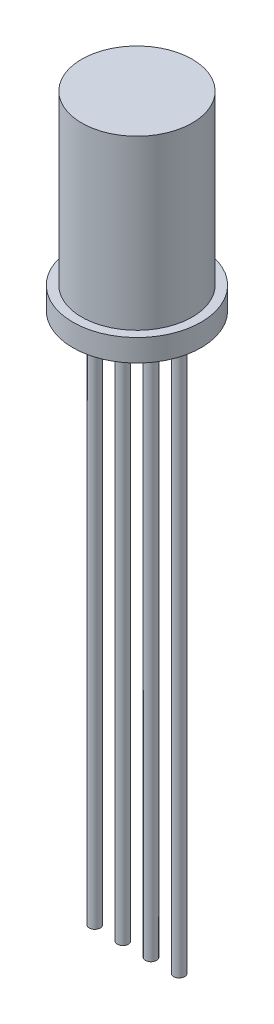
SolidWorks part; units mm, degrees
ref_plane "Front Plane" through (0, 0, 0) normal (0, 0, 1) x (1, 0, 0)
ref_plane "Top Plane" through (0, 0, 0) normal (0, 1, 0) x (1, 0, 0)
ref_plane "Right Plane" through (0, 0, 0) normal (1, 0, 0) x (0, 0, -1)
sketch "SK Leads" plane through (0, 0, 0) normal (0, 1, 0) x (1, 0, 0)
  circle A0 centre (-1.905, 0) radius 0.25
  circle A1 centre (-0.635, 0) radius 0.25
  circle A2 centre (0.635, 0) radius 0.25
  circle A3 centre (1.905, 0) radius 0.25
extrude "Leads" add sketch "SK Leads" along normal blind 25 from offset 25 separate body
sketch "SK Flange" plane through (0, 0, 0) normal (0, 1, 0) x (1, 0, 0)
  circle A0 centre (0, 0) radius 2.9
extrude "Flange" add sketch "SK Flange" along normal blind 1 separate body
sketch "SK Lens" plane through (0, 0, 0) normal (0, 1, 0) x (1, 0, 0)
  circle A0 centre (0, 0) radius 2.5
extrude "Lens" add sketch "SK Lens" along normal blind 7.6 from offset 1 separate body
